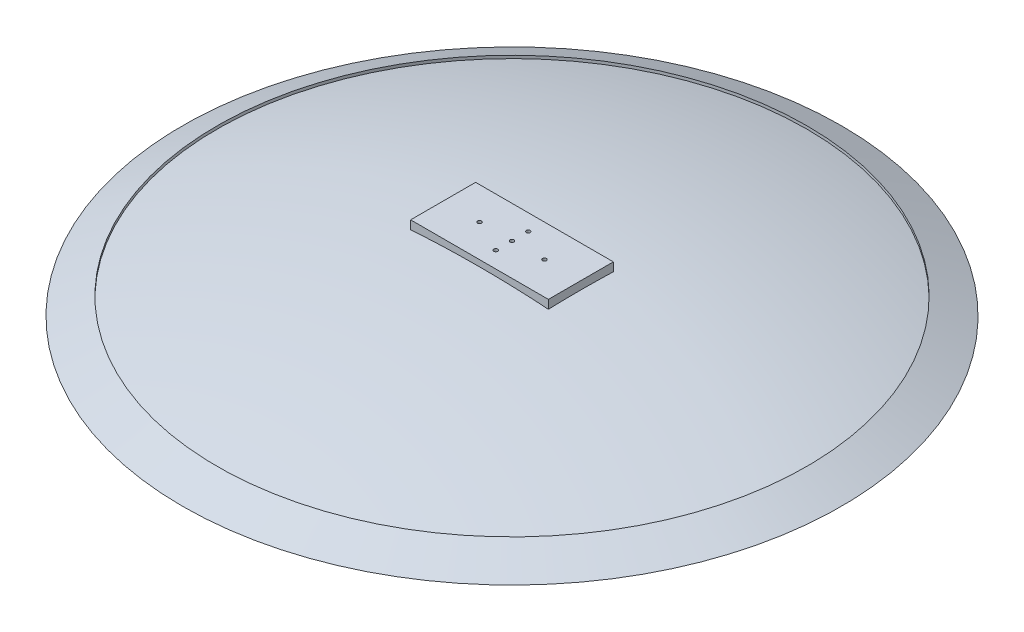
SolidWorks part; units mm, degrees
ref_plane "Alzado" through (0, 0, 0) normal (0, 0, 1) x (1, 0, 0)
ref_plane "Planta" through (0, 0, 0) normal (0, 1, 0) x (1, 0, 0)
ref_plane "Vista lateral" through (0, 0, 0) normal (1, 0, 0) x (0, 0, -1)
sketch "Croquis1" plane through (0, 0, 0) normal (0, 0, 1) x (1, 0, 0)
  line L0 (446, 461.866) -> (953.2542, 208.812) construction
  line L8 (450, 300) -> (900, 300) construction
  line L9 (900, 300) -> (900, 230.9088) construction
  line L12 (900, 235.3789) -> (953.2542, 208.812)
  line L13 (446, 295.9947) -> (446, 300)
  line L14 (450, 300) -> (446, 300)
  line L15 (900, 230.9088) -> (900, 235.3789)
  line L16 (446, 295.9947) -> (446, 461.866) construction
  line L17 (450, 300) -> (450, 455.4004) construction
  line L18 (450, 455.4004) -> (900, 230.9088) construction
  arc A2 (450, 300) -> (900, 230.9088) centre (450, -1200) cw
  arc A3 (446, 295.9947) -> (953.2542, 208.812) centre (450, -1200) cw
  point P7 (450, 300)
  dimension "D3" = 4
  dimension "D1" = 450
revolve "Revolución6" add sketch "Croquis1" angle 360 about L13
sketch "Croquis7" plane through (0, 0, 0) normal (0, 1, 0) x (1, 0, 0)
  line L1 (340, -50) -> (552, -50)
  line L2 (340, -50) -> (340, 50)
  line L3 (340, 50) -> (552, 50)
  line L4 (552, -50) -> (552, 50)
  point P0 (446, 0)
  dimension "D1" = 100
  dimension "D2" = 212
extrude "Saliente-Extruir4" add sketch "Croquis7" along normal blind 14 from offset 295
sketch "Croquis8" plane through (0, 309, 0) normal (0, 1, 0) x (1, 0, 0)
  line L0 (446, 50) -> (446, -50) construction
  line L1 (552, 50) -> (340, 50) construction
  line L2 (340, -50) -> (552, -50) construction
  line L3 (340, 0) -> (552, 0) construction
  line L4 (340, 50) -> (340, -50) construction
  line L5 (552, -50) -> (552, 50) construction
  line L6 (396, 0) -> (496, 0)
  line L7 (446, -25) -> (446, 25)
  circle A0 centre (446, 25) radius 3
  circle A1 centre (496, 0) radius 3
  circle A2 centre (396, 0) radius 3
  circle A3 centre (446, -25) radius 3
  circle A4 centre (446, 0) radius 3
  point P15 (446, 0)
  point P18 (446, 0)
  dimension "D3" = 6
  dimension "D4" = 6
  dimension "D5" = 6
  dimension "D6" = 6
  dimension "D7" = 6
  dimension "D1" = 50
  dimension "D2" = 100
extrude "Cortar-Extruir3" cut sketch "Croquis8" against normal blind 24
